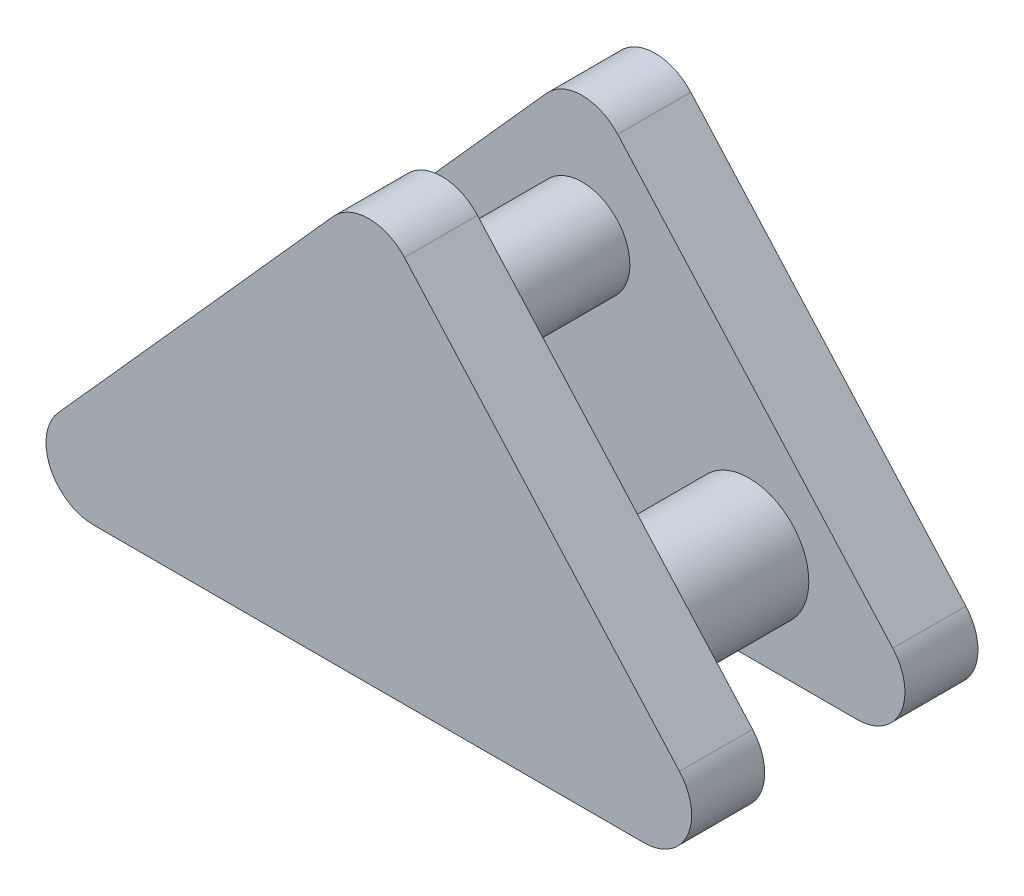
SolidWorks part; units mm, degrees
ref_plane "Front Plane" through (0, 0, 0) normal (0, 0, 1) x (1, 0, 0)
ref_plane "Top Plane" through (0, 0, 0) normal (0, 1, 0) x (1, 0, 0)
ref_plane "Right Plane" through (0, 0, 0) normal (1, 0, 0) x (0, 0, -1)
sketch "Sketch1" plane through (0, 0, 0) normal (0, 0, 1) x (1, 0, 0)
  line L0 (-8, 0) -> (8, 0)
  line L1 (8, 0) -> (0, 8.9443)
  line L2 (0, 8.9443) -> (-8, 0)
  dimension "D1" = 16
  dimension "D2" = 8
  dimension "D3" = 12
  dimension "D4" = 12
extrude "Boss-Extrude1" add sketch "Sketch1" along normal blind 6
sketch "Sketch2" plane through (0, 0, 0) normal (1, 0, 0) x (0, 0, -1)
  line L0 (-4.4694, 8.9443) -> (-1.5306, 8.9443)
  line L1 (-6, 8.9443) -> (0, 8.9443) construction
  line L2 (-1.5306, 8.9443) -> (-1.5306, 0)
  line L3 (-6, 0) -> (0, 0) construction
  line L4 (-1.5306, 0) -> (-4.4694, 0)
  line L5 (-4.4694, 0) -> (-4.4694, 8.9443)
  dimension "D1" = 1.5306
extrude "Cut-Extrude1" cut sketch "Sketch2" against normal through all both and the other way through all
sketch "Sketch3" plane through (0, 0, 0) normal (0, 0, 1) x (1, 0, 0)
  line L0 (-8, 0) -> (8, 0) construction
  circle A0 centre (0, 5.8746) radius 1
  circle A1 centre (-3.5, 2) radius 1.25
  circle A2 centre (3.5, 2) radius 1.25
  dimension "D1" = 2
  dimension "D2" = 2.5
  dimension "D3" = 2.5
  dimension "D4" = 3.5
  dimension "D5" = 3.5
  dimension "D6" = 2
  dimension "D7" = 2
extrude "Boss-Extrude2" add sketch "Sketch3" along normal blind 6
fillet "Fillet1" radius 1 6 edges at (-8, 0, 5.2347) (-8, 0, 0.7653) (0, 8.9443, 5.2347) (8, 0, 5.2347) (8, 0, 0.7653) (0, 8.9443, 0.7653)
